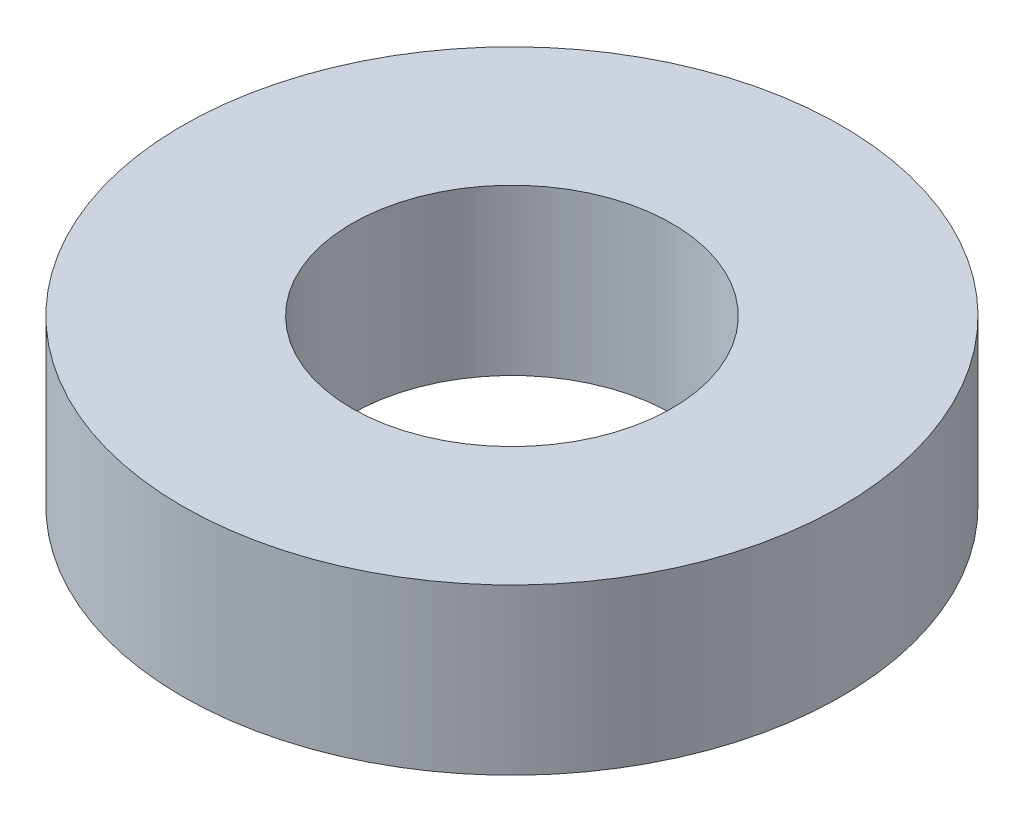
SolidWorks part; units mm, degrees
ref_plane "Front Plane" through (0, 0, 0) normal (0, 0, 1) x (1, 0, 0)
ref_plane "Top Plane" through (0, 0, 0) normal (0, 1, 0) x (1, 0, 0)
ref_plane "Right Plane" through (0, 0, 0) normal (1, 0, 0) x (0, 0, -1)
sketch "Sketch1" plane through (0, 0, 0) normal (0, 1, 0) x (1, 0, 0)
  circle A0 centre (0, 0) radius 1.7
  circle A1 centre (0, 0) radius 3.5
  dimension "D1" = 3.4
  dimension "D2" = 7
extrude "Boss-Extrude1" add sketch "Sketch1" along normal blind 1.75
